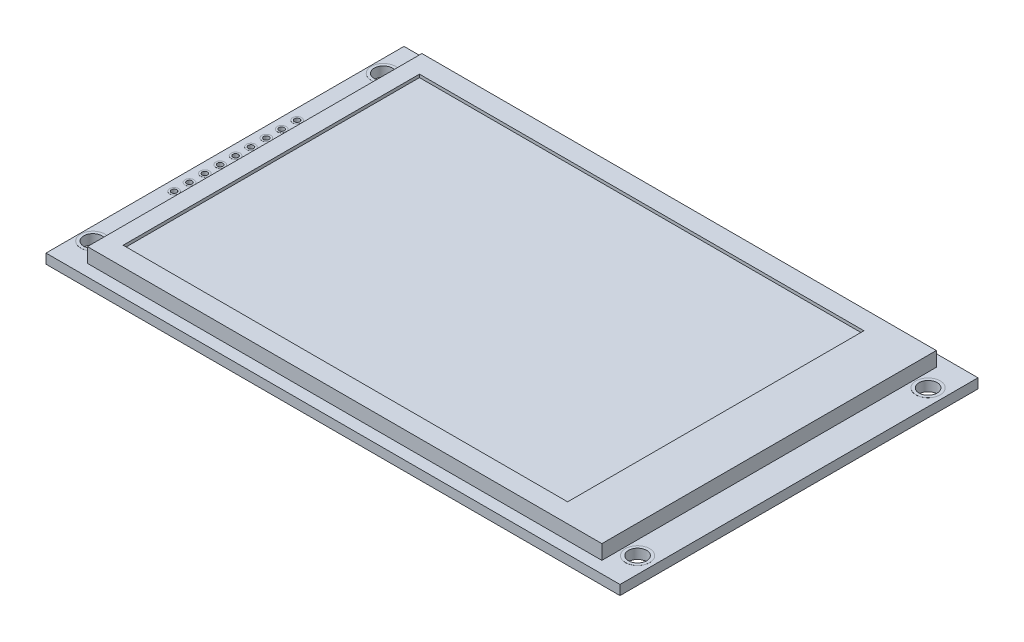
SolidWorks part; units mm, degrees
ref_plane "Piano frontale" through (0, 0, 0) normal (0, 0, 1) x (1, 0, 0)
ref_plane "Piano superiore" through (0, 0, 0) normal (0, 1, 0) x (1, 0, 0)
ref_plane "Piano destro" through (0, 0, 0) normal (1, 0, 0) x (0, 0, -1)
sketch "Schizzo1" plane through (0, 0, 0) normal (0, 1, 0) x (1, 0, 0)
  line L0 (-86.7678, 0) -> (79.809, 0) construction
  line L2 (-47.42, 29.575) -> (47.42, 29.575)
  line L3 (-47.42, 29.575) -> (-47.42, -29.575)
  line L4 (-47.42, -29.575) -> (47.42, -29.575)
  line L5 (47.42, 29.575) -> (47.42, -29.575)
  line L6 (-47.42, 29.575) -> (47.42, -29.575) construction
  line L7 (-47.42, -29.575) -> (47.42, 29.575) construction
  point P3 (0, 0)
  dimension "D1" = 59.15
  dimension "D2" = 94.84
extrude "Estrusione-Estrusione1" add sketch "Schizzo1" along normal mid plane 1.6
sketch "Schizzo2" plane through (0, 0.8, 0) normal (0, 1, 0) x (1, 0, 0)
  line L0 (-57.2452, 0) -> (58.5504, 0) construction
  line L1 (0, 35.6151) -> (0, -39.0647) construction
  line L2 (47.42, -29.575) -> (47.42, 29.575) construction
  line L7 (-45.26, 24) -> (44.75, 24) construction
  line L9 (-45.26, 24) -> (-45.26, -24) construction
  line L10 (-45.26, -24) -> (44.75, -24) construction
  line L11 (44.75, 24) -> (44.75, -24) construction
  line L12 (-45.26, 24) -> (44.75, -24) construction
  line L13 (-45.26, -24) -> (44.75, 24) construction
  circle A0 centre (-45.26, 24) radius 1.5
  circle A1 centre (44.75, 24) radius 1.5
  circle A2 centre (44.75, -24) radius 1.5
  circle A3 centre (-45.26, -24) radius 1.5
  point P5 (-0.255, 0)
  dimension "D4" = 3
  dimension "D1" = 2.67
  dimension "D2" = 48
  dimension "D3" = 90.01
extrude "Taglio-Estrusione1" cut sketch "Schizzo2" against normal through all
sketch "Schizzo3" plane through (0, 0.8, 0) normal (0, 1, 0) x (1, 0, 0)
  line L0 (-53.8343, 0) -> (14.1801, 0) construction
  line L1 (-45.67, 32.7053) -> (-45.67, -31.0102) construction
  line L2 (-47.42, 29.575) -> (-47.42, -29.575) construction
  circle A0 centre (-45.67, 0) radius 0.445
  circle A1 centre (-45.67, -2.54) radius 0.445
  circle A2 centre (-45.67, -5.08) radius 0.445
  circle A3 centre (-45.67, -7.62) radius 0.445
  circle A4 centre (-45.67, -10.16) radius 0.445
  circle A5 centre (-45.67, 2.54) radius 0.445
  circle A6 centre (-45.67, 5.08) radius 0.445
  circle A7 centre (-45.67, 7.62) radius 0.445
  circle A8 centre (-45.67, 10.16) radius 0.445
  dimension "D2" = 0.89
  dimension "D1" = 1.75
  dimension "D3" = 5
  dimension "D4" = 5
extrude "Taglio-Estrusione2" cut sketch "Schizzo3" against normal through all
sketch "Schizzo4" plane through (0, 0.8, 0) normal (0, 1, 0) x (1, 0, 0)
  circle A0 centre (-45.67, 10.16) radius 0.445 construction
  circle A1 centre (-45.67, 7.62) radius 0.445 construction
  circle A2 centre (-45.67, 5.08) radius 0.445 construction
  circle A3 centre (-45.67, 2.54) radius 0.445 construction
  circle A4 centre (-45.67, 0) radius 0.445 construction
  circle A5 centre (-45.67, -2.54) radius 0.445 construction
  circle A6 centre (-45.67, -5.08) radius 0.445 construction
  circle A7 centre (-45.67, -7.62) radius 0.445 construction
  circle A8 centre (-45.67, -10.16) radius 0.445 construction
  circle A9 centre (-45.26, -24) radius 1.5 construction
  circle A10 centre (44.75, -24) radius 1.5 construction
  circle A11 centre (44.75, 24) radius 1.5 construction
  circle A12 centre (-45.26, 24) radius 1.5 construction
  circle A13 centre (-45.67, 10.16) radius 0.445
  circle A14 centre (-45.67, 7.62) radius 0.445
  circle A15 centre (-45.67, 5.08) radius 0.445
  circle A16 centre (-45.67, 2.54) radius 0.445
  circle A17 centre (-45.67, 0) radius 0.445
  circle A18 centre (-45.67, -2.54) radius 0.445
  circle A19 centre (-45.67, -5.08) radius 0.445
  circle A20 centre (-45.67, -7.62) radius 0.445
  circle A21 centre (-45.67, -10.16) radius 0.445
  circle A22 centre (-45.26, -24) radius 1.5
  circle A23 centre (44.75, -24) radius 1.5
  circle A24 centre (44.75, 24) radius 1.5
  circle A25 centre (-45.26, 24) radius 1.5
  circle A26 centre (44.75, 24) radius 2
  circle A27 centre (-45.26, 24) radius 2
  circle A28 centre (-45.26, -24) radius 2
  circle A29 centre (44.75, -24) radius 2
  circle A30 centre (-45.67, 10.16) radius 0.745
  circle A31 centre (-45.67, 7.62) radius 0.745
  circle A32 centre (-45.67, 5.08) radius 0.745
  circle A33 centre (-45.67, 2.54) radius 0.745
  circle A34 centre (-45.67, 0) radius 0.745
  circle A35 centre (-45.67, -2.54) radius 0.745
  circle A36 centre (-45.67, -5.08) radius 0.745
  circle A37 centre (-45.67, -7.62) radius 0.745
  circle A38 centre (-45.67, -10.16) radius 0.745
  dimension "D1" = 0.5
  dimension "D2" = 0.3
extrude "Estrusione-Estrusione2" add sketch "Schizzo4" along normal blind 0.01
mirror "Specchia1" about plane through (0, 0, 0) normal (0, 1, 0) of "Estrusione-Estrusione2"
sketch "Schizzo5" plane through (0, 0.8, 0) normal (0, 1, 0) x (1, 0, 0)
  line L0 (-57.2452, 0) -> (56.4993, 0) construction
  line L1 (-42.52, 27.63) -> (42.48, 27.63)
  line L2 (-42.52, 27.63) -> (-42.52, -27.63)
  line L3 (-42.52, -27.63) -> (42.48, -27.63)
  line L4 (42.48, 27.63) -> (42.48, -27.63)
  line L5 (-42.52, 27.63) -> (42.48, -27.63) construction
  line L6 (-42.52, -27.63) -> (42.48, 27.63) construction
  line L7 (-47.42, 29.575) -> (-47.42, -29.575) construction
  point P0 (-0.02, 0)
  point P8 (0, 0)
  dimension "D1" = 55.26
  dimension "D2" = 85
  dimension "D3" = 4.9
extrude "Estrusione-Estrusione3" add sketch "Schizzo5" along normal blind 2.4
sketch "Schizzo7" plane through (0, 3.2, 0) normal (0, 1, 0) x (1, 0, 0)
  line L0 (-60.2286, 0) -> (55.2873, 0) construction
  line L1 (-42.52, 27.63) -> (-42.52, -27.63) construction
  line L2 (-39.77, 24.48) -> (33.67, 24.48)
  line L3 (-39.77, 24.48) -> (-39.77, -24.48)
  line L4 (-39.77, -24.48) -> (33.67, -24.48)
  line L5 (33.67, 24.48) -> (33.67, -24.48)
  line L6 (-39.77, 24.48) -> (33.67, -24.48) construction
  line L7 (-39.77, -24.48) -> (33.67, 24.48) construction
  point P3 (-3.05, 0)
  dimension "D1" = 2.75
  dimension "D2" = 73.44
  dimension "D3" = 48.96
extrude "Taglio-Estrusione3" cut sketch "Schizzo7" against normal blind 0.5
